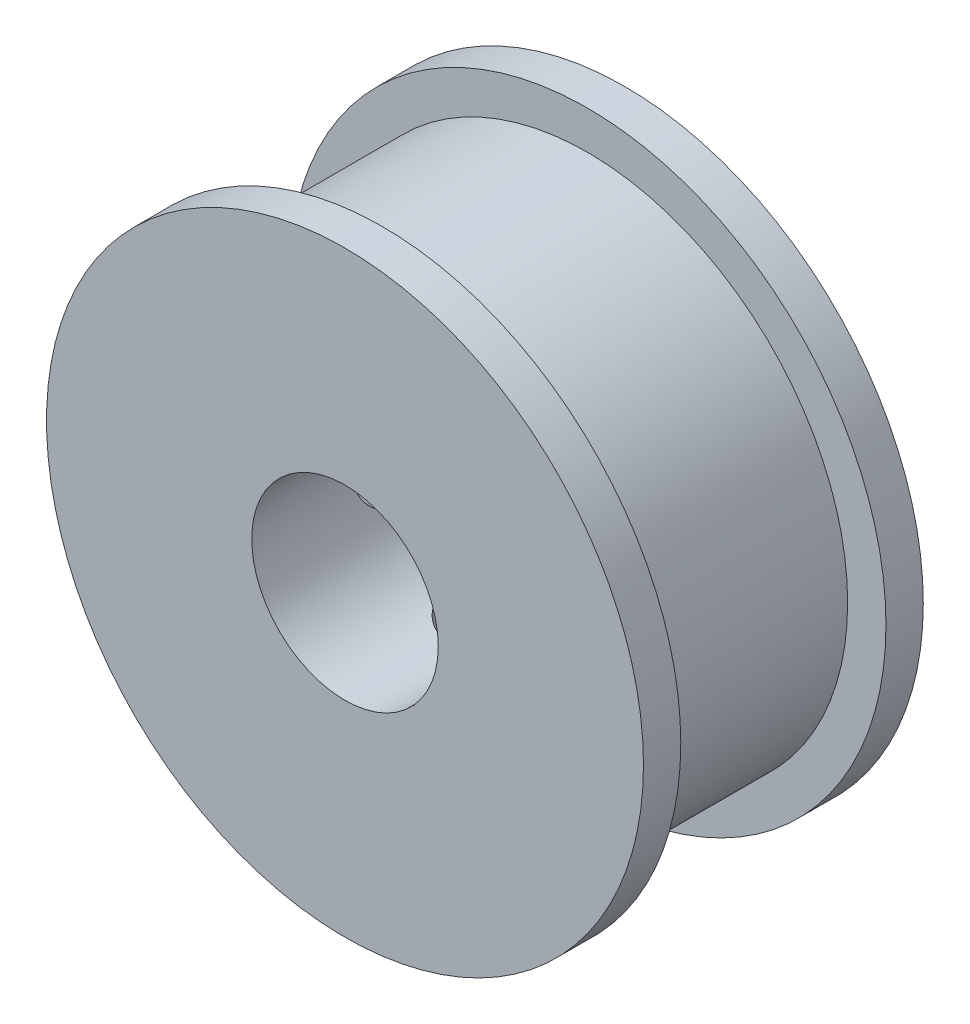
SolidWorks part; units mm, degrees
ref_plane "前视基准面" through (0, 0, 0) normal (0, 0, 1) x (1, 0, 0)
ref_plane "上视基准面" through (0, 0, 0) normal (0, 1, 0) x (1, 0, 0)
ref_plane "右视基准面" through (0, 0, 0) normal (1, 0, 0) x (0, 0, -1)
sketch "草图1" plane through (0, 0, 0) normal (0, 0, 1) x (1, 0, 0)
  circle A0 centre (0, 0) radius 16
  dimension "D1" = 32
extrude "凸台-拉伸1" add sketch "草图1" along normal blind 2 contours A0
sketch "草图2" plane through (0, 0, 2) normal (0, 0, 1) x (1, 0, 0)
  circle A0 centre (0, 0) radius 13.945
  dimension "D1" = 27.89
extrude "凸台-拉伸2" add sketch "草图2" along normal blind 11
sketch "草图3" plane through (0, 0, 13) normal (0, 0, 1) x (1, 0, 0)
  circle A0 centre (0, 0) radius 16
  dimension "D1" = 32
extrude "凸台-拉伸3" add sketch "草图3" along normal blind 2
sketch "草图4" plane through (0, 0, 15) normal (0, 0, 1) x (1, 0, 0)
  circle A0 centre (0, 0) radius 5
  dimension "D1" = 10
extrude "切除-拉伸1" cut sketch "草图4" against normal blind 15
sketch "草图5" plane through (0, 0, 0) normal (0, 1, 0) x (1, 0, 0)
  line L0 (0, 0) -> (0, -15) construction
  line L1 (-16, -15) -> (16, -15) construction
  circle A0 centre (0, -7.5) radius 2
extrude "切除-拉伸2" cut sketch "草图5" against normal blind 20
sketch "草图8" plane through (0, 0, 0) normal (1, 0, 0) x (0, 0, -1)
  line L0 (-15, 0) -> (0, 0) construction
  line L1 (-15, 16) -> (-15, -16) construction
  circle A0 centre (-7.5, 0) radius 2
extrude "切除-拉伸3" cut sketch "草图8" against normal blind 20
